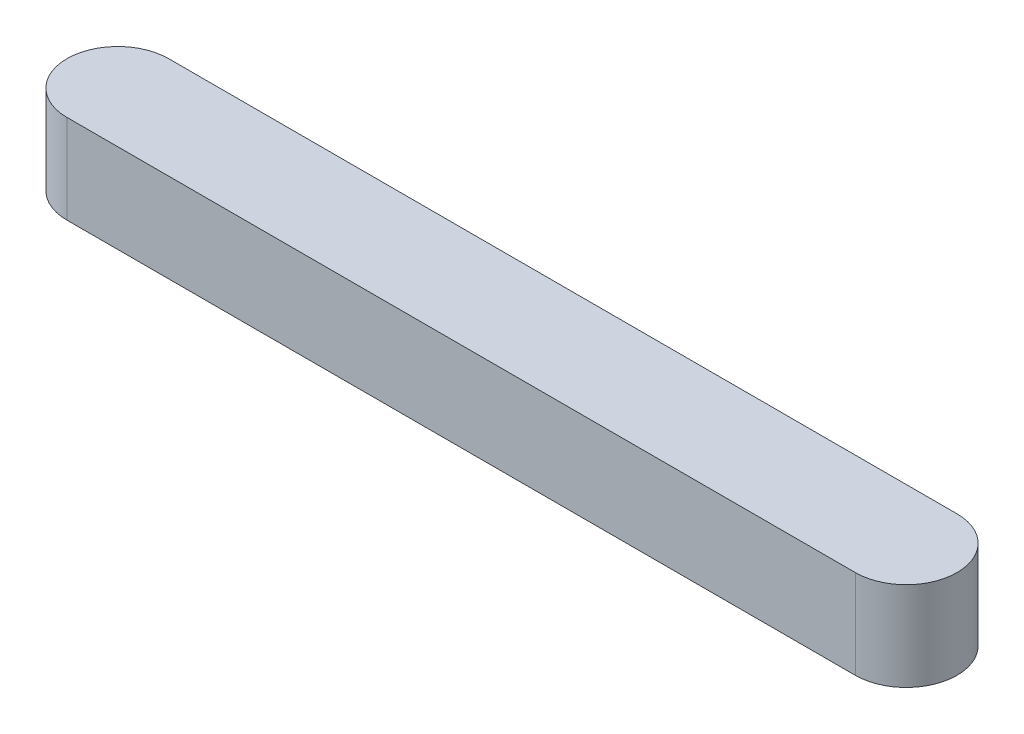
SolidWorks part; units mm, degrees
ref_plane "Спереди" through (0, 0, 0) normal (0, 0, 1) x (1, 0, 0)
ref_plane "Сверху" through (0, 0, 0) normal (0, 1, 0) x (1, 0, 0)
ref_plane "Справа" through (0, 0, 0) normal (1, 0, 0) x (0, 0, -1)
sketch "Эскиз1" plane through (0, 0, 0) normal (0, 1, 0) x (1, 0, 0)
  line L0 (0, 0) -> (62, 0) construction
  line L2 (0, 4) -> (62, 4)
  line L3 (0, -4) -> (62, -4)
  arc A0 (0, 4) -> (0, -4) centre (0, 0) ccw
  arc A1 (62, -4) -> (62, 4) centre (62, 0) ccw
  point P5 (31, 0)
extrude "Бобышка-Вытянуть1" add sketch "Эскиз1" along normal blind 7
